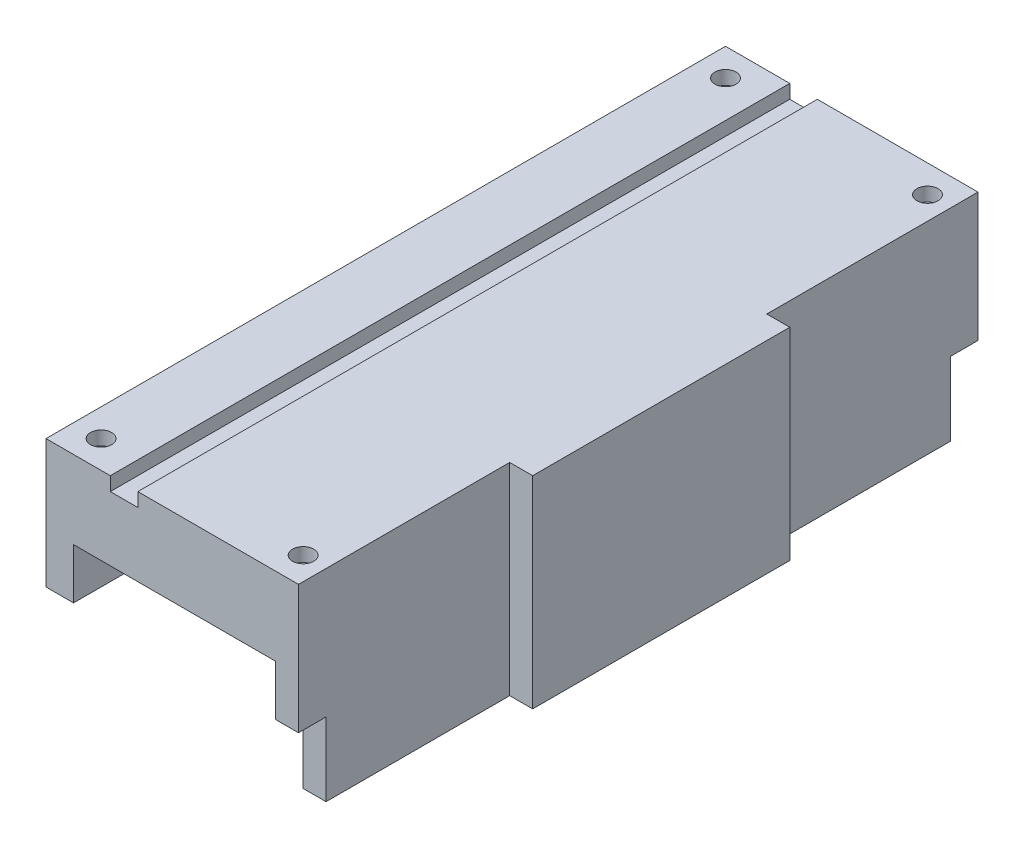
SolidWorks part; units mm, degrees
ref_plane "Front Plane" through (0, 0, 0) normal (0, 0, 1) x (1, 0, 0)
ref_plane "Top Plane" through (0, 0, 0) normal (0, 1, 0) x (1, 0, 0)
ref_plane "Right Plane" through (0, 0, 0) normal (1, 0, 0) x (0, 0, -1)
sketch "Sketch1" plane through (0, 0, 0) normal (0, 1, 0) x (1, 0, 0)
  line L0 (11.5, 14) -> (11.5, -14)
  line L1 (14, -14) -> (-14, -14)
  line L2 (14, -14) -> (14, 14)
  line L3 (14, 14) -> (-14, 14)
  line L4 (-14, -14) -> (-14, 14)
  line L5 (0, 14) -> (0, -14) construction
  line L6 (14, 0) -> (-14, 0) construction
  line L7 (9, -34) -> (14, -34)
  line L12 (0, 34) -> (0, -34) construction
  line L13 (-9, 0) -> (9, 0) construction
  line L14 (9, -34) -> (9, 34)
  line L15 (9, 34) -> (14, 34)
  line L16 (14, -34) -> (14, 34)
  line L17 (11.5, 34) -> (11.5, -34) construction
  line L18 (9, 0) -> (14, 0) construction
  line L19 (11.5, 34) -> (11.5, -34)
  point P0 (0, 0)
  point P4 (11.5, 0)
  point P6 (0, 0)
  dimension "D1" = 28
  dimension "D2" = 28
  dimension "D3" = 5
extrude "Boss-Extrude1" add sketch "Sketch1" along normal blind 22 contours L2 L3 L0 L1 | L14 L1 L0 L3 | L19 L1 L14 L7 | L19 L15 L14 L3
sketch "Sketch2" plane through (9, 0, 0) normal (-1, 0, 0) x (0, 0, 1)
  line L0 (-34, 22) -> (-34, 0) construction
  line L1 (-34, 22) -> (34, 22)
  line L2 (-34, 22) -> (-34, 19)
  line L3 (-34, 19) -> (34, 19)
  line L4 (34, 22) -> (34, 19)
  line L5 (34, 22) -> (34, 0) construction
  line L6 (34, 22) -> (-34, 22) construction
  dimension "D1" = 3
  dimension "D2" = 0
extrude "Boss-Extrude2" add sketch "Sketch2" along normal blind 22
sketch "Sketch3" plane through (0, 22, 0) normal (0, 1, 0) x (1, 0, 0)
  line L1 (11.5, 34) -> (-13, 34)
  line L2 (11.5, 34) -> (11.5, -34)
  line L3 (11.5, -34) -> (-13, -34)
  line L4 (-13, 34) -> (-13, -34)
  line L5 (11.5, -37) -> (-16, -37)
  line L6 (-16, 37) -> (-16, -37)
  line L7 (11.5, 37) -> (-16, 37)
  line L8 (11.5, 37) -> (11.5, -37)
  line L9 (14.5, -37) -> (-16, -37) construction
  line L10 (14.5, 37) -> (14.5, -37) construction
  line L11 (14.5, 37) -> (-16, 37) construction
  line M4 (11.5, 34) -> (-13, 34)
  line M5 (-13, 34) -> (-13, -34)
  line M6 (-13, -34) -> (11.5, -34)
  dimension "D1" = 3
extrude "Boss-Extrude3" add sketch "Sketch3" against normal blind 14 contours L8 L7 L6 L5 M6 M5 M4
sketch "Sketch4" plane through (0, 0, 37) normal (0, 0, 1) x (1, 0, 0)
  line L0 (-13, 19) -> (9, 8) construction
  line L1 (-11, 13.5) -> (7, 13.5)
  line L2 (7, 8) -> (-11, 8)
  line L4 (11.5, 22) -> (-16, 22)
  line L5 (-16, 22) -> (-16, 8)
  line L6 (-16, 8) -> (11.5, 8)
  line L7 (11.5, 8) -> (11.5, 22)
  line L8 (11.5, 22) -> (-16, 22)
  line L9 (-16, 22) -> (-16, 8)
  line L10 (-16, 8) -> (11.5, 8)
  line L11 (11.5, 8) -> (11.5, 22)
  line L12 (9, 8) -> (9, 19)
  line L13 (-13, 8) -> (9, 8)
  line L14 (-13, 19) -> (-13, 8)
  line L15 (9, 19) -> (-13, 19)
  line L16 (9, 8) -> (9, 19)
  line L17 (-13, 8) -> (9, 8)
  line L18 (-13, 19) -> (-13, 8)
  line L19 (9, 19) -> (-13, 19)
  line L20 (7, 19) -> (-11, 19)
  line L22 (-2, 19) -> (-2, 8) construction
  line L23 (7, 13.5) -> (-11, 13.5) construction
  line L24 (-11, 13.5) -> (-13, 13.5)
  line L25 (-13, 13.5) -> (9, 13.5)
  point P6 (-2, 13.5)
  dimension "D4" = 11
  dimension "D1" = 0
  dimension "D2" = 0
extrude "Cut-Extrude1" cut sketch "Sketch4" against normal blind 10
sketch "Sketch5" plane through (0, 22, 0) normal (0, 1, 0) x (1, 0, 0)
  line L0 (-13, 34) -> (-13, 37)
  line L2 (-6, -37) -> (-9, -37)
  line L3 (-6, -37) -> (-6, 37)
  line L4 (9, -34) -> (9, 34)
  line L5 (-13, -34) -> (9, -34)
  line L6 (-13, 34) -> (-13, -34)
  line L7 (9, 34) -> (-13, 34)
  line L8 (11.5, 14) -> (11.5, 37)
  line L9 (11.5, 37) -> (-16, 37)
  line L10 (-16, 37) -> (-16, -37)
  line L11 (-16, -37) -> (11.5, -37)
  line L12 (11.5, -37) -> (11.5, -14)
  line L13 (11.5, -14) -> (14, -14)
  line L14 (14, -14) -> (14, 14)
  line L15 (14, 14) -> (11.5, 14)
  line L16 (11.5, 14) -> (11.5, 37)
  line L17 (11.5, 37) -> (-16, 37)
  line L18 (-16, 37) -> (-16, -37)
  line L19 (-16, -37) -> (11.5, -37)
  line L20 (11.5, -37) -> (11.5, -14)
  line L21 (11.5, -14) -> (14, -14)
  line L22 (14, -14) -> (14, 14)
  line L23 (14, 14) -> (11.5, 14)
  line L24 (9, -34) -> (9, 34)
  line L25 (-13, -34) -> (9, -34)
  line L26 (-13, 34) -> (-13, -34)
  line L27 (9, 34) -> (-13, 34)
  line L28 (-6, 37) -> (-9, 37)
  line L29 (-9, -37) -> (-9, 37)
  line L30 (-7.5, 37) -> (-7.5, -37) construction
  line L31 (-6, 0) -> (-9, 0) construction
  circle A0 centre (9, 34) radius 1.15
  circle A1 centre (9, -34) radius 1.15
  circle A2 centre (-13, -34) radius 1.15
  circle A3 centre (-13, 34) radius 1.15
  point P6 (-7.5, 0)
  dimension "D5" = 2.3
  dimension "D6" = 2.3
  dimension "D7" = 2.3
  dimension "D8" = 2.3
  dimension "D3" = 3
  dimension "D4" = 7
  dimension "D1" = 0
  dimension "D2" = 0
extrude "Cut-Extrude2" cut sketch "Sketch5" against normal blind 1.5 contours L3 L2 L29 L28 | A3 | A0 | A1 | A2
